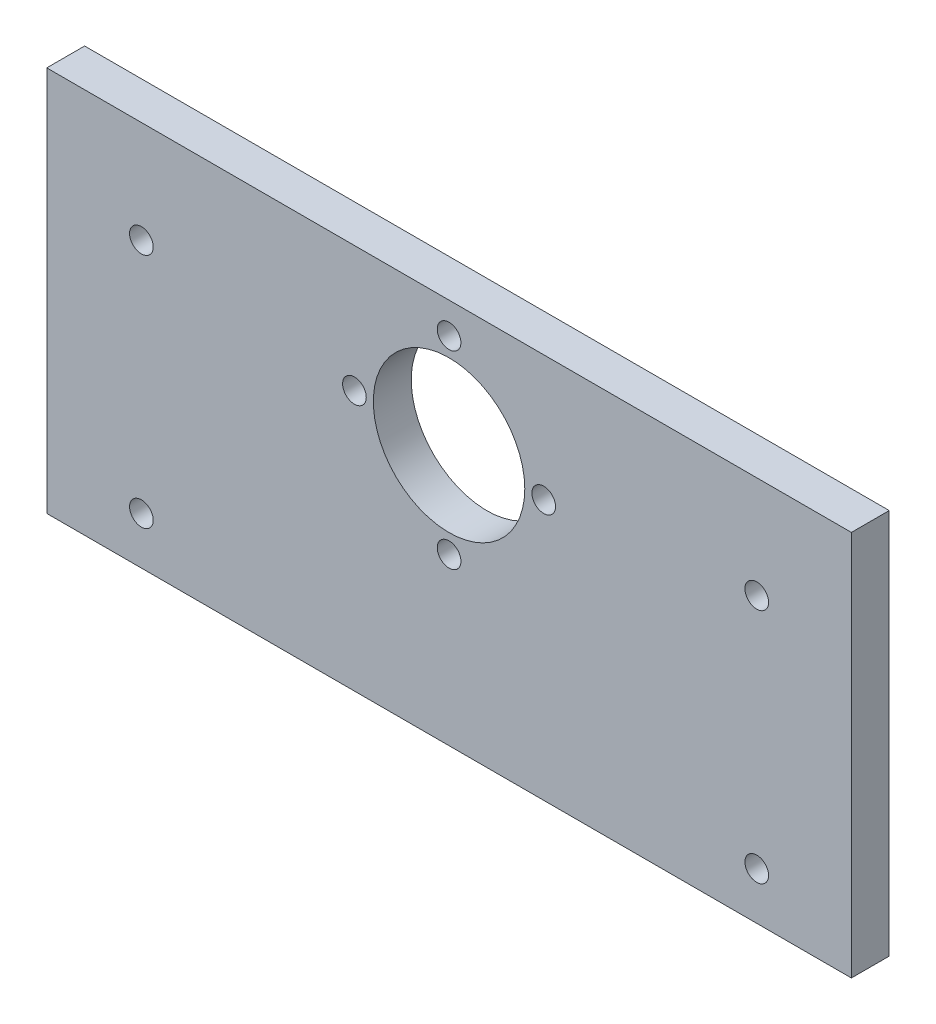
SolidWorks part; units mm, degrees
ref_plane "Front Plane" through (0, 0, 0) normal (0, 0, 1) x (1, 0, 0)
ref_plane "Top Plane" through (0, 0, 0) normal (0, 1, 0) x (1, 0, 0)
ref_plane "Right Plane" through (0, 0, 0) normal (1, 0, 0) x (0, 0, -1)
sketch "Sketch1" plane through (0, 0, 0) normal (0, 0, 1) x (1, 0, 0)
  line L1 (-85.0178, -83.3072) -> (85.0178, -83.3072)
  line L2 (-85.0178, -83.3072) -> (-85.0178, 83.3072)
  line L3 (-85.0178, 83.3072) -> (85.0178, 83.3072)
  line L4 (85.0178, -83.3072) -> (85.0178, 83.3072)
  line L5 (-85.0178, -83.3072) -> (85.0178, 83.3072) construction
  line L6 (-85.0178, 83.3072) -> (85.0178, -83.3072) construction
  circle A0 centre (0, 0) radius 16
  point P0 (0, 0)
extrude "Boss-Extrude1" add sketch "Sketch1" along normal blind 8
sketch "Sketch2" plane through (0, 0, 8) normal (0, 0, 1) x (1, 0, 0)
  line L0 (-85.0178, 83.3072) -> (-85.0178, -83.3072) construction
  line L1 (-85.0178, 26.5477) -> (85.0178, 26.5477)
  line L2 (-85.0178, 26.5477) -> (-85.0178, 83.3072)
  line L3 (-85.0178, 83.3072) -> (85.0178, 83.3072)
  line L4 (85.0178, 26.5477) -> (85.0178, 83.3072)
  line L6 (-85.0178, -55) -> (85.0178, -55)
  line L7 (-85.0178, -55) -> (-85.0178, -83.3072)
  line L8 (-85.0178, -83.3072) -> (85.0178, -83.3072)
  line L9 (85.0178, -55) -> (85.0178, -83.3072)
  circle A0 centre (-65.0178, 5) radius 2.5
  circle A1 centre (-65.0178, -45) radius 2.5
  circle A2 centre (65.0178, 5) radius 2.5
  circle A3 centre (65.0178, -45) radius 2.5
  circle A4 centre (0, 20) radius 2.5 construction
  circle A5 centre (0, 20) radius 2.5
  circle A6 centre (-20, 0) radius 2.5
  circle A7 centre (0, -20) radius 2.5
  circle A8 centre (20, 0) radius 2.5
  dimension "D1" = 5
extrude "Cut-Extrude1" cut sketch "Sketch2" against normal through all
